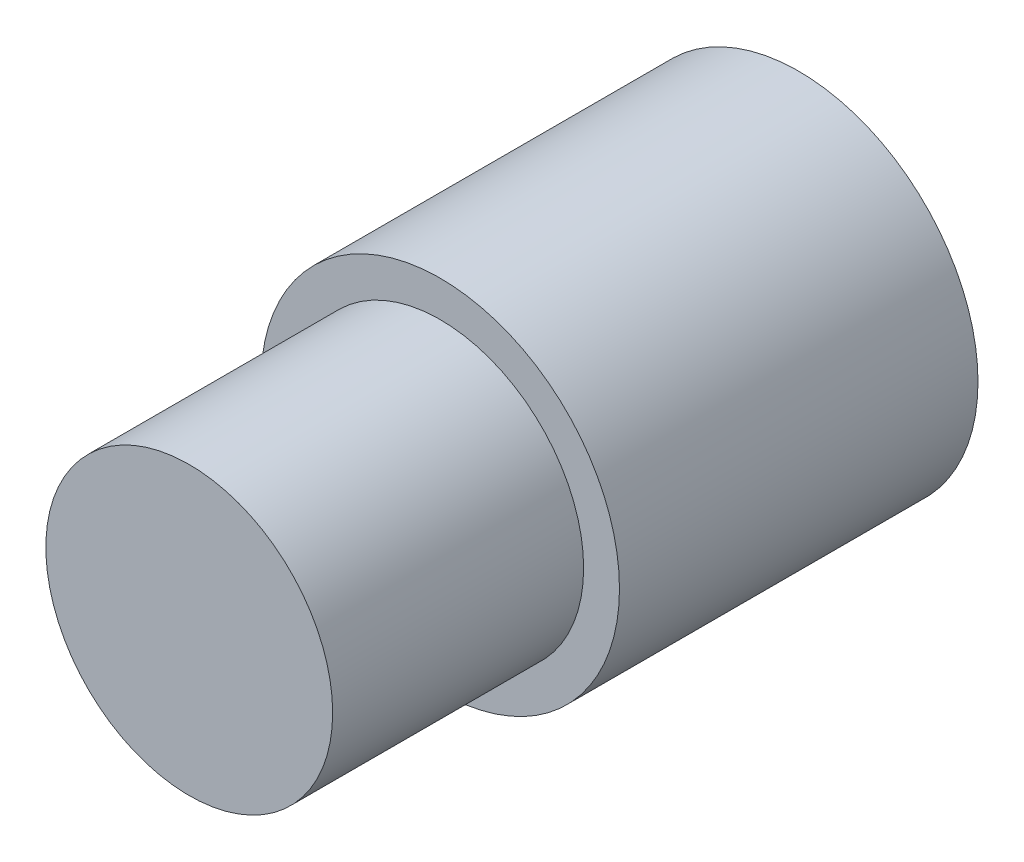
SolidWorks part; units mm, degrees
ref_plane "Front Plane" through (0, 0, 0) normal (0, 0, 1) x (1, 0, 0)
ref_plane "Top Plane" through (0, 0, 0) normal (0, 1, 0) x (1, 0, 0)
ref_plane "Right Plane" through (0, 0, 0) normal (1, 0, 0) x (0, 0, -1)
sketch "Sketch1" plane through (0, 0, 0) normal (0, 0, 1) x (1, 0, 0)
  circle A0 centre (0, 0) radius 5
  circle A1 centre (0, 0) radius 1.5
  dimension "D1" = 10
  dimension "D2" = 3
extrude "Boss-Extrude1" add sketch "Sketch1" along normal blind 10
sketch "Sketch2" plane through (0, 0, 10) normal (0, 0, 1) x (1, 0, 0)
  circle A0 centre (0, 0) radius 4
  dimension "D1" = 8
extrude "Boss-Extrude2" add sketch "Sketch2" along normal blind 7
